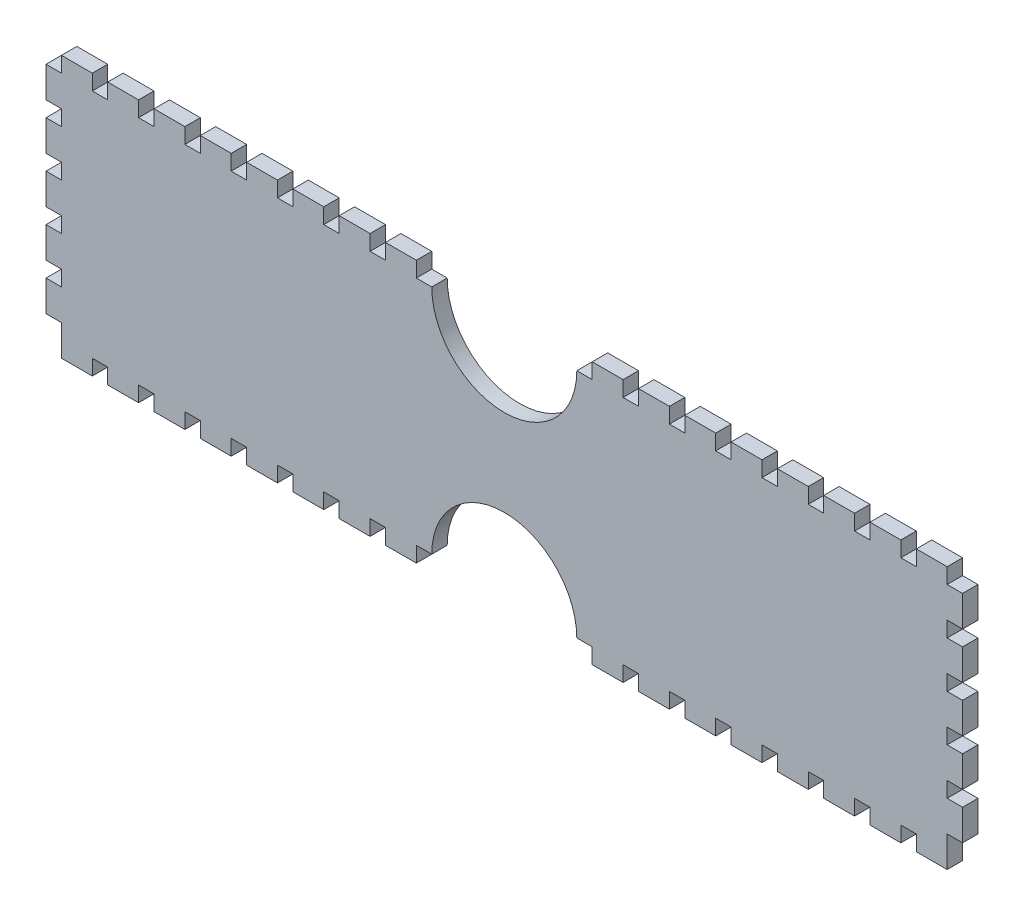
SolidWorks part; units mm, degrees
ref_plane "Plan de face" through (0, 0, 0) normal (0, 0, 1) x (1, 0, 0)
ref_plane "Plan de dessus" through (0, 0, 0) normal (0, 1, 0) x (1, 0, 0)
ref_plane "Plan de droite" through (0, 0, 0) normal (1, 0, 0) x (0, 0, -1)
sketch "Esquisse1" plane through (0, 0, 0) normal (0, 0, 1) x (1, 0, 0)
  line L1 (-164.9057, -20.6439) -> (132.0943, -20.6439)
  line L2 (-164.9057, -20.6439) -> (-164.9057, 64.3561)
  line L3 (-164.9057, 64.3561) -> (132.0943, 64.3561)
  line L4 (132.0943, -20.6439) -> (132.0943, 64.3561)
  line L5 (-164.9057, -20.6439) -> (132.0943, 64.3561) construction
  line L6 (-164.9057, 64.3561) -> (132.0943, -20.6439) construction
  dimension "D1" = 85
extrude "Boss.-Extru.1" add sketch "Esquisse1" along normal blind 5
sketch "Esquisse4" plane through (0, 0, 5) normal (0, 0, 1) x (1, 0, 0)
  line L1 (-164.9057, 64.3561) -> (-159.9057, 64.3561)
  line L2 (-164.9057, 64.3561) -> (-164.9057, 59.3561)
  line L3 (-164.9057, 59.3561) -> (-159.9057, 59.3561)
  line L4 (-159.9057, 64.3561) -> (-159.9057, 59.3561)
  point P4 (-164.9057, 64.3561)
  dimension "D1" = 5
  dimension "D2" = 5
extrude "Enlèv. mat.-Extru.2" cut sketch "Esquisse4" against normal up to next
pattern_linear "Répétition linéaire1" count 6 spacing 15 along (0, -1, 0) of "Enlèv. mat.-Extru.2"
sketch "Esquisse5" plane through (0, 0, 5) normal (0, 0, 1) x (1, 0, 0)
  line L1 (-159.9057, -15.6439) -> (-164.9057, -15.6439)
  line L2 (-159.9057, -15.6439) -> (-159.9057, -20.6439)
  line L3 (-159.9057, -20.6439) -> (-164.9057, -20.6439)
  line L4 (-164.9057, -15.6439) -> (-164.9057, -20.6439)
extrude "Enlèv. mat.-Extru.3" cut sketch "Esquisse5" against normal blind 5
ref_plane "Plan1" through (-16.4057, 0, 0) normal (-1, 0, 0) x (0, 0, 1)
sketch "Esquisse6" plane through (0, 0, 5) normal (0, 0, 1) x (1, 0, 0)
  line L1 (132.0943, 64.3561) -> (127.0943, 64.3561)
  line L2 (132.0943, 64.3561) -> (132.0943, 59.3561)
  line L3 (132.0943, 59.3561) -> (127.0943, 59.3561)
  line L4 (127.0943, 64.3561) -> (127.0943, 59.3561)
  point P4 (132.0943, 64.3561)
  dimension "D1" = 5
  dimension "D2" = 5
extrude "Enlèv. mat.-Extru.4" cut sketch "Esquisse6" against normal blind 5
pattern_linear "Répétition linéaire5" count 6 spacing 15 along (0, -1, 0) of "Enlèv. mat.-Extru.4"
ref_plane "Plan2" through (127.0943, -15.6439, 5) normal (1, 0, 0) x (0, 0, -1)
sketch "Esquisse8" plane through (0, 0, 5) normal (0, 0, 1) x (1, 0, 0)
  line L0 (132.0943, -20.6439) -> (132.0943, -15.6439) construction
  line L1 (127.0943, -15.6439) -> (132.0943, -15.6439)
  line L2 (127.0943, -15.6439) -> (127.0943, -20.6439)
  line L3 (127.0943, -20.6439) -> (132.0943, -20.6439)
  line L4 (132.0943, -15.6439) -> (132.0943, -20.6439)
  line L5 (-159.9057, -20.6439) -> (132.0943, -20.6439) construction
extrude "Enlèv. mat.-Extru.5" cut sketch "Esquisse8" against normal blind 5
sketch "Esquisse9" plane through (0, 0, 5) normal (0, 0, 1) x (1, 0, 0)
  line L1 (-159.9057, -20.6439) -> (127.0943, -20.6439) construction
  line L2 (-149.9057, -20.6439) -> (-144.9057, -20.6439)
  line L3 (-149.9057, -20.6439) -> (-149.9057, -15.6439)
  line L4 (-149.9057, -15.6439) -> (-144.9057, -15.6439)
  line L6 (-159.9057, -20.6439) -> (-159.9057, -10.6439) construction
  line L7 (-144.9057, -20.6439) -> (-144.9057, -15.6439)
  dimension "D1" = 5
  dimension "D2" = 10
  dimension "D3" = 5
extrude "Enlèv. mat.-Extru.6" cut sketch "Esquisse9" against normal blind 5
pattern_linear "Répétition linéaire7" count 8 spacing 15 along (1, 0, 0) of "Enlèv. mat.-Extru.6"
mirror "Symétrie5" about plane through (-16.4057, 0, 0) normal (-1, 0, 0) of "Répétition linéaire7", "Enlèv. mat.-Extru.6"
sketch "Esquisse11" plane through (0, 0, 5) normal (0, 0, 1) x (1, 0, 0)
  line L0 (127.0943, 64.3561) -> (-159.9057, 64.3561) construction
  line L1 (-39.9057, 64.3561) -> (7.0943, 64.3561)
  line L2 (-39.9057, 64.3561) -> (-39.9057, 59.3561)
  line L3 (-39.9057, 59.3561) -> (7.0943, 59.3561)
  line L4 (7.0943, 64.3561) -> (7.0943, 59.3561)
  arc A0 (7.0943, 59.3561) -> (-39.9057, 59.3561) centre (-16.4057, 59.3561) cw
  point P8 (-16.4057, 64.3561)
  point P9 (-16.4057, 64.3561)
  dimension "D1" = 5
  dimension "D2" = 47
extrude "Enlèv. mat.-Extru.7" cut sketch "Esquisse11" against normal blind 5 contours A0 L3 | L4 L1 L2 L3
sketch "Esquisse12" plane through (0, 0, 5) normal (0, 0, 1) x (1, 0, 0)
  line L1 (-39.9057, -15.6439) -> (7.0943, -15.6439)
  line L2 (-39.9057, -15.6439) -> (-39.9057, -64.3561)
  line L3 (-39.9057, -64.3561) -> (7.0943, -64.3561)
  line L4 (7.0943, -15.6439) -> (7.0943, -64.3561)
  arc A0 (-39.9057, -15.6439) -> (7.0943, -15.6439) centre (-16.4057, -15.6439) cw
extrude "Enlèv. mat.-Extru.8" cut sketch "Esquisse12" against normal blind 10 contours L4 L1 L2 L3 | A0 L1
ref_plane "Plan3" through (0, 21.8561, 0) normal (0, 1, 0) x (1, 0, 0)
mirror "Symétrie6" about plane through (0, 21.8561, 0) normal (0, 1, 0) of "Symétrie5", "Enlèv. mat.-Extru.6", "Répétition linéaire7"
